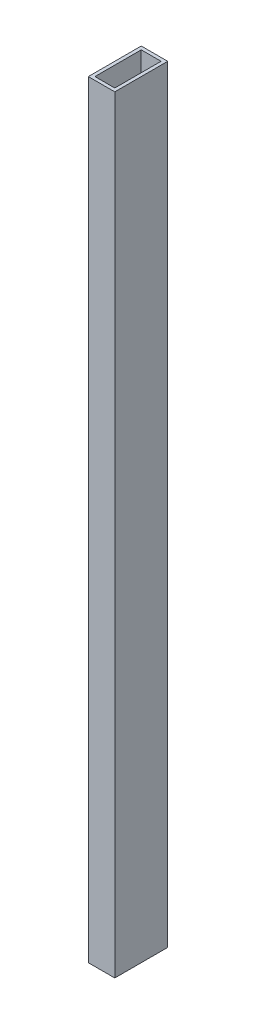
SolidWorks part; units mm, degrees
ref_plane "Front Plane" through (0, 0, 0) normal (0, 0, 1) x (1, 0, 0)
ref_plane "Top Plane" through (0, 0, 0) normal (0, 1, 0) x (1, 0, 0)
ref_plane "Right Plane" through (0, 0, 0) normal (1, 0, 0) x (0, 0, -1)
sketch "Sketch1" plane through (0, 0, 0) normal (0, 1, 0) x (1, 0, 0)
  line L0 (-9.525, -22.225) -> (-9.525, 22.225)
  line L1 (-12.7, -25.4) -> (12.7, -25.4)
  line L2 (-12.7, -25.4) -> (-12.7, 25.4)
  line L3 (-12.7, 25.4) -> (12.7, 25.4)
  line L4 (12.7, -25.4) -> (12.7, 25.4)
  line L5 (-12.7, -25.4) -> (12.7, 25.4) construction
  line L6 (-12.7, 25.4) -> (12.7, -25.4) construction
  line L7 (-9.525, 22.225) -> (9.525, 22.225)
  line L8 (9.525, -22.225) -> (9.525, 22.225)
  line L9 (-9.525, -22.225) -> (9.525, -22.225)
  point P0 (0, 0)
  dimension "D1" = 25.4
  dimension "D2" = 50.8
  dimension "D3" = 3.175
extrude "Boss-Extrude1" add sketch "Sketch1" along normal blind 736.6
